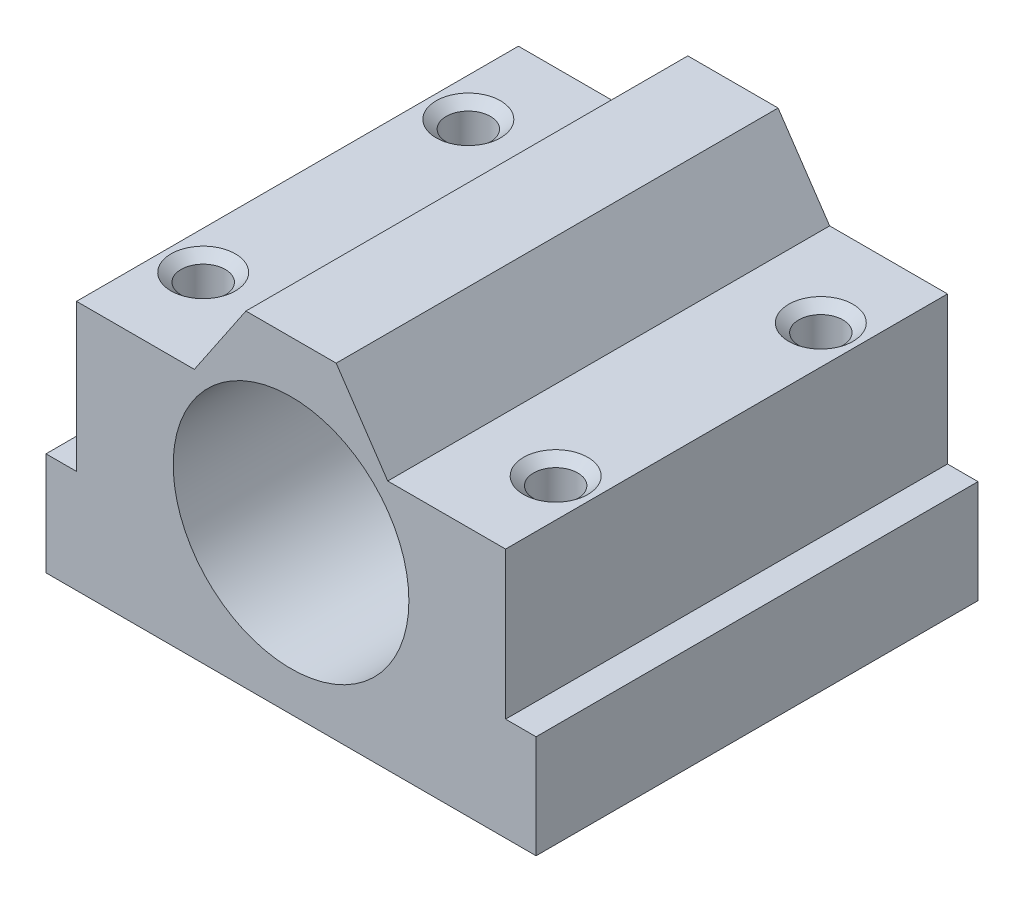
SolidWorks part; units mm, degrees
ref_plane "Front Plane" through (0, 0, 0) normal (0, 0, 1) x (1, 0, 0)
ref_plane "Top Plane" through (0, 0, 0) normal (0, 1, 0) x (1, 0, 0)
ref_plane "Right Plane" through (0, 0, 0) normal (1, 0, 0) x (0, 0, -1)
sketch "Sketch1" plane through (0, 0, 0) normal (0, 0, 1) x (1, 0, 0)
  line L5 (33.27, 7) -> (31.1994, 7)
  line L7 (31.1994, 7) -> (31.1994, 17)
  line L8 (33.27, 0) -> (33.27, 7)
  line L9 (31.1994, 17) -> (23.1994, 17)
  line L11 (0, 0) -> (33.27, 0)
  line L13 (2.0706, 17) -> (10.0706, 17)
  line L14 (2.0706, 7) -> (2.0706, 17)
  line L15 (0, 7) -> (2.0706, 7)
  line L16 (0, 0) -> (0, 7)
  line L17 (13.5706, 22.18) -> (19.6994, 22.18)
  line L18 (23.1994, 17) -> (19.6994, 22.18)
  line L20 (10.0706, 17) -> (13.5706, 22.18)
  circle A0 centre (16.635, 10.68) radius 8 construction
  circle A1 centre (16.635, 10.68) radius 8
  dimension "D1" = 16.635
  dimension "D2" = 10.68
  dimension "D3" = 16
extrude "Boss-Extrude1" add sketch "Sketch1" along normal blind 30
sketch "Sketch2" plane through (0, 17, 0) normal (0, 1, 0) x (1, 0, 0)
  circle A0 centre (28.5994, -6) radius 1.5
  circle A1 centre (28.5994, -24) radius 1.5
  circle A2 centre (4.6706, -24) radius 1.5
  circle A3 centre (4.6706, -6) radius 1.5
extrude "Cut-Extrude2" cut sketch "Sketch2" against normal blind 30
hole_wizard "CSK for #2 Flat Head Machine Screw (100)1" positions "Sketch8" profile "Sketch9" countersink size "#2" standard "ANSI Inch" end condition through all
sketch "Sketch8" plane through (0, 17, 0) normal (0, 1, 0) x (1, 0, 0)
  point P0 (4.6706, -6)
sketch "Sketch9" plane through (4.6706, 17, 6) normal (1, 0, 0) x (0, 0, 1)
  line L0 (0, 0) -> (0, 17)
  line L1 (0, 17) -> (1.3525, 17)
  line L2 (1.3525, 17) -> (1.3525, 0.698)
  line L3 (1.3525, 0.698) -> (2.1844, 0)
  line L5 (2.1844, 0) -> (0, 0)
  line L6 (-1.3525, 0.698) -> (-2.1844, 0) construction
  line L11 (0, -6.35) -> (0, 107.95) construction
  dimension "Thru Hole Dia." = 2.7051
  dimension "Thru Hole Depth" = 17
  dimension "Near C'Sink Dia." = 4.3688
  dimension "Near C'Sink Angle" = 100
hole_wizard "CSK for #2 Flat Head Machine Screw (100)2" positions "Sketch10" profile "Sketch11" countersink size "#2" standard "ANSI Inch" end condition through all
sketch "Sketch10" plane through (0, 17, 0) normal (0, 1, 0) x (1, 0, 0)
  point P0 (4.6706, -24)
sketch "Sketch11" plane through (4.6706, 17, 24) normal (1, 0, 0) x (0, 0, 1)
  line L0 (0, 0) -> (0, 17)
  line L1 (0, 17) -> (1.3525, 17)
  line L2 (1.3525, 17) -> (1.3525, 0.698)
  line L3 (1.3525, 0.698) -> (2.1844, 0)
  line L5 (2.1844, 0) -> (0, 0)
  line L6 (-1.3525, 0.698) -> (-2.1844, 0) construction
  line L11 (0, -6.35) -> (0, 107.95) construction
  dimension "Thru Hole Dia." = 2.7051
  dimension "Thru Hole Depth" = 17
  dimension "Near C'Sink Dia." = 4.3688
  dimension "Near C'Sink Angle" = 100
hole_wizard "CSK for #2 Flat Head Machine Screw (100)3" positions "Sketch12" profile "Sketch13" countersink size "#2" standard "ANSI Inch" end condition through all
sketch "Sketch12" plane through (0, 17, 0) normal (0, 1, 0) x (1, 0, 0)
  point P0 (28.5994, -6)
sketch "Sketch13" plane through (28.5994, 17, 6) normal (1, 0, 0) x (0, 0, 1)
  line L0 (0, 0) -> (0, 17)
  line L1 (0, 17) -> (1.3525, 17)
  line L2 (1.3525, 17) -> (1.3525, 0.698)
  line L3 (1.3525, 0.698) -> (2.1844, 0)
  line L5 (2.1844, 0) -> (0, 0)
  line L6 (-1.3525, 0.698) -> (-2.1844, 0) construction
  line L11 (0, -6.35) -> (0, 107.95) construction
  dimension "Thru Hole Dia." = 2.7051
  dimension "Thru Hole Depth" = 17
  dimension "Near C'Sink Dia." = 4.3688
  dimension "Near C'Sink Angle" = 100
hole_wizard "CSK for #2 Flat Head Machine Screw (100)4" positions "Sketch14" profile "Sketch15" countersink size "#2" standard "ANSI Inch" end condition through all
sketch "Sketch14" plane through (0, 17, 0) normal (0, 1, 0) x (1, 0, 0)
  point P0 (28.5994, -24)
sketch "Sketch15" plane through (28.5994, 17, 24) normal (1, 0, 0) x (0, 0, 1)
  line L0 (0, 0) -> (0, 17)
  line L1 (0, 17) -> (1.3525, 17)
  line L2 (1.3525, 17) -> (1.3525, 0.698)
  line L3 (1.3525, 0.698) -> (2.1844, 0)
  line L5 (2.1844, 0) -> (0, 0)
  line L6 (-1.3525, 0.698) -> (-2.1844, 0) construction
  line L11 (0, -6.35) -> (0, 107.95) construction
  dimension "Thru Hole Dia." = 2.7051
  dimension "Thru Hole Depth" = 17
  dimension "Near C'Sink Dia." = 4.3688
  dimension "Near C'Sink Angle" = 100
